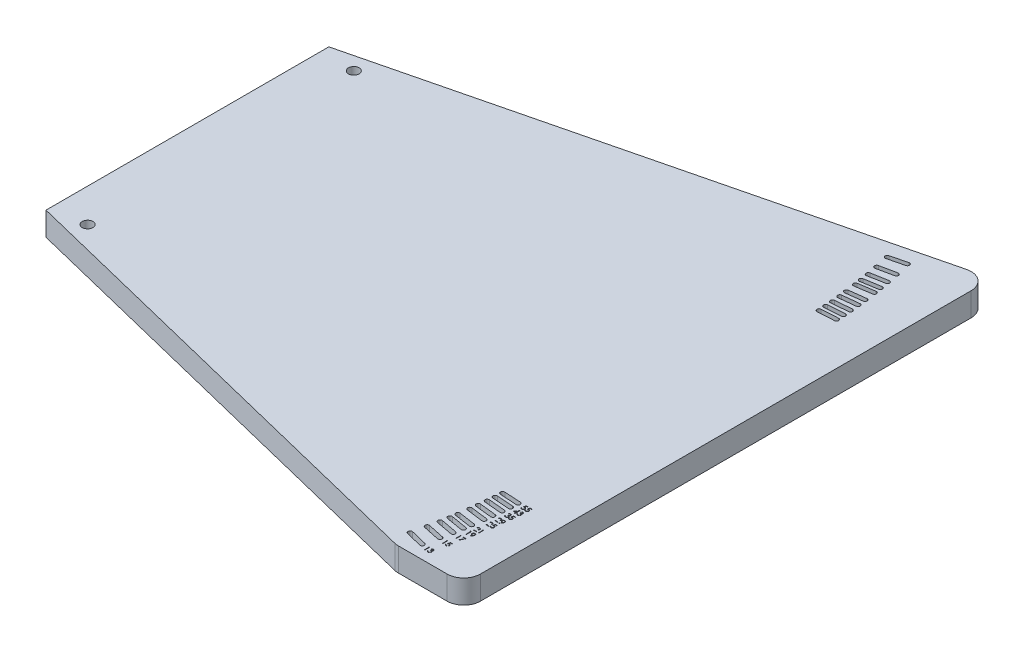
SolidWorks part; units mm, degrees
ref_plane "Front" through (0, 0, 0) normal (0, 0, 1) x (1, 0, 0)
ref_plane "Top" through (0, 0, 0) normal (0, 1, 0) x (1, 0, 0)
ref_plane "Right" through (0, 0, 0) normal (1, 0, 0) x (0, 0, -1)
sketch "Sketch1" plane through (0, 0, 0) normal (0, 1, 0) x (1, 0, 0)
  line L0 (0, 107.95) -> (0, -107.95)
  line L1 (0, -107.95) -> (406.4, -208.1174)
  line L2 (406.4, -208.1174) -> (406.4, 208.1174)
  line L3 (406.4, 208.1174) -> (0, 107.95)
  line L4 (25.4, 101.6) -> (25.4, -101.6) construction
  line L5 (25.4, 0) -> (0, 0) construction
  line L6 (25.4, 0) -> (406.4, 0) construction
  circle A0 centre (25.4, 101.6) radius 4.064
  circle A1 centre (25.4, -101.6) radius 4.064
  dimension "D1" = 8.128
  dimension "D2" = 203.2
  dimension "D3" = 103.846
  dimension "D4" = 25.4
  dimension "D5" = 406.4
  dimension "D6" = 215.9
extrude "Boss-Extrude1" add sketch "Sketch1" along normal blind 17.9832
sketch "Sketch2" plane through (0, 17.9832, 0) normal (0, 1, 0) x (1, 0, 0)
  line L0 (406.4, -208.1174) -> (406.4, 208.1174) construction
  line L1 (406.4, -195.4174) -> (354.8735, -195.4174)
  line L2 (406.4, -195.4174) -> (406.4, -208.1174)
  line L3 (406.4, -208.1174) -> (354.8735, -208.1174)
  line L4 (354.8735, -195.4174) -> (354.8735, -208.1174)
  line L5 (0, -107.95) -> (406.4, -208.1174) construction
  dimension "D1" = 12.7
extrude "Cut-Extrude1" cut sketch "Sketch2" against normal blind 17.9832
fillet "Fillet1" radius 12.7 3 edges at (406.4, 8.9916, -208.1174) (406.4, 8.9916, 195.4174) (354.8735, 8.9916, 195.4174)
sketch "Sketch3" plane through (0, 17.9832, 0) normal (0, 1, 0) x (1, 0, 0)
  line L0 (25.4, -101.6) -> (366.9196, -132.3373) construction
  line L1 (25.4, -101.6) -> (364.4701, -152.7066) construction
  line L2 (25.4, 101.6) -> (25.4, -101.6) construction
  line L3 (25.4, -101.6) -> (358.336, -183.6613) construction
  line L4 (25.4, 0) -> (406.4, 0) construction
  line L5 (406.4, -182.7174) -> (406.4, 191.9071) construction
  line L6 (25.4, -101.6) -> (363.6233, -158.0395) construction
  line L7 (25.4, -101.6) -> (365.5961, -144.5768) construction
  line L8 (25.4, -101.6) -> (367.7408, -121.1758) construction
  line L9 (25.4, -101.6) -> (360.8068, -172.8929) construction
  line L11 (364.5014, -185.181) -> (352.1705, -182.1417) construction
  line L12 (25.4, -101.6) -> (362.4615, -164.6077) construction
  line L13 (364.1215, -186.7223) -> (351.7906, -183.683)
  line L14 (364.8813, -183.6396) -> (352.5504, -180.6003)
  line L15 (367.018, -174.2132) -> (354.5956, -171.5727) construction
  line L16 (366.688, -175.766) -> (354.2655, -173.1255)
  line L17 (367.3481, -172.6603) -> (354.9256, -170.0199)
  line L18 (368.7033, -165.7745) -> (356.2196, -163.4409) construction
  line L19 (368.4116, -167.335) -> (355.9279, -165.0014)
  line L20 (368.9951, -164.2141) -> (356.5113, -161.8805)
  line L21 (371.8961, -145.3726) -> (359.2962, -143.7809) construction
  line L22 (371.6971, -146.9476) -> (359.0972, -145.3559)
  line L23 (372.095, -143.7976) -> (359.4952, -142.2059)
  line L27 (370.7492, -153.653) -> (358.191, -151.7602) construction
  line L28 (370.5126, -155.2228) -> (357.9544, -153.3299)
  line L29 (370.9858, -152.0832) -> (358.4276, -150.1904)
  line L30 (374.0804, -121.5383) -> (361.4011, -120.8132) construction
  line L31 (373.9898, -123.1232) -> (361.3105, -122.3981)
  line L32 (374.171, -119.9534) -> (361.4918, -119.2283)
  line L33 (373.244, -132.9065) -> (360.5951, -131.7681) construction
  line L34 (373.1017, -134.4876) -> (360.4528, -133.3492)
  line L35 (373.3863, -131.3254) -> (360.7375, -130.187)
  line L36 (369.8867, -159.0847) -> (357.3599, -156.9943) construction
  line L37 (369.6254, -160.6505) -> (357.0986, -158.5602)
  line L38 (370.148, -157.5188) -> (357.6212, -155.4285)
  line L55 (25.4, -101.6) -> (367.3852, -126.6301) construction
  line L68 (373.7183, -127.0936) -> (361.0522, -126.1666) construction
  line L69 (373.6024, -128.6769) -> (360.9363, -127.7498)
  line L70 (373.8342, -125.5104) -> (361.1681, -124.5833)
  line L71 (25.4, -101.6) -> (366.2899, -138.674) construction
  line L72 (372.6027, -139.3606) -> (359.9771, -137.9875) construction
  line L73 (372.431, -140.9388) -> (359.8055, -139.5657)
  line L74 (372.7743, -137.7824) -> (360.1488, -136.4093)
  arc A0 (364.1215, -186.7223) -> (364.8813, -183.6396) centre (364.5014, -185.181) ccw
  arc A1 (352.5504, -180.6003) -> (351.7906, -183.683) centre (352.1705, -182.1417) ccw
  arc A2 (366.688, -175.766) -> (367.3481, -172.6603) centre (367.018, -174.2132) ccw
  arc A3 (354.9256, -170.0199) -> (354.2655, -173.1255) centre (354.5956, -171.5727) ccw
  arc A4 (368.4116, -167.335) -> (368.9951, -164.2141) centre (368.7033, -165.7745) ccw
  arc A5 (356.5113, -161.8805) -> (355.9279, -165.0014) centre (356.2196, -163.4409) ccw
  arc A6 (371.6971, -146.9476) -> (372.095, -143.7976) centre (371.8961, -145.3726) ccw
  arc A7 (359.4952, -142.2059) -> (359.0972, -145.3559) centre (359.2962, -143.7809) ccw
  arc A10 (370.5126, -155.2228) -> (370.9858, -152.0832) centre (370.7492, -153.653) ccw
  arc A11 (358.4276, -150.1904) -> (357.9544, -153.3299) centre (358.191, -151.7602) ccw
  arc A12 (373.9898, -123.1232) -> (374.171, -119.9534) centre (374.0804, -121.5383) ccw
  arc A13 (361.4918, -119.2283) -> (361.3105, -122.3981) centre (361.4011, -120.8132) ccw
  arc A14 (373.1017, -134.4876) -> (373.3863, -131.3254) centre (373.244, -132.9065) ccw
  arc A15 (360.7375, -130.187) -> (360.4528, -133.3492) centre (360.5951, -131.7681) ccw
  arc A16 (369.6254, -160.6505) -> (370.148, -157.5188) centre (369.8867, -159.0847) ccw
  arc A17 (357.6212, -155.4285) -> (357.0986, -158.5602) centre (357.3599, -156.9943) ccw
  arc A32 (373.6024, -128.6769) -> (373.8342, -125.5104) centre (373.7183, -127.0936) ccw
  arc A33 (361.1681, -124.5833) -> (360.9363, -127.7498) centre (361.0522, -126.1666) ccw
  arc A34 (372.431, -140.9388) -> (372.7743, -137.7824) centre (372.6027, -139.3606) ccw
  arc A35 (360.1488, -136.4093) -> (359.8055, -139.5657) centre (359.9771, -137.9875) ccw
  point P18 (358.336, -183.6613)
  point P25 (360.8068, -172.8929)
  point P33 (362.4615, -164.6077)
  point P39 (365.5961, -144.5768)
  point P53 (364.4701, -152.7066)
  point P61 (367.7408, -121.1758)
  point P67 (366.9196, -132.3373)
  point P76 (363.6233, -158.0395)
  point P140 (367.3852, -126.6301)
  point P148 (366.2899, -138.674)
  dimension "D1" = 342.9
  dimension "D3" = 12
  dimension "D4" = 10.588
  dimension "D5" = 7.2
  dimension "D2" = 13.846
  dimension "D7" = 8.571
  dimension "D8" = 3.273
  dimension "D9" = 5.143
  dimension "D10" = 12.7
  dimension "D11" = 3.175
  dimension "D13" = 9.474
  dimension "D21" = 4.186
  dimension "D22" = 6.207
extrude "Magic Cut" cut sketch "Sketch3" against normal through all
mirror "Mirror1" about plane through (0, 0, 0) normal (0, 0, 1) of "Magic Cut"
sketch "Sketch5" plane through (0, 17.9832, 0) normal (0, 1, 0) x (1, 0, 0)
  line L0 (364.5014, -185.181) -> (367.6686, -188.2231) construction
  line L1 (368.7033, -165.7745) -> (372.0383, -168.6318) construction
  line L2 (367.018, -174.2132) -> (370.2816, -177.1517) construction
  line L3 (371.8961, -145.3726) -> (375.394, -148.0277) construction
  line L4 (369.8867, -159.0847) -> (373.2766, -161.8765) construction
  line L5 (374.0804, -121.5383) -> (377.752, -123.9476) construction
  line L6 (373.244, -132.9065) -> (376.8351, -135.4344) construction
  line L7 (373.7183, -127.0936) -> (377.351, -129.5611) construction
  line L8 (370.7492, -153.653) -> (374.1826, -156.3911) construction
  line L9 (372.6027, -139.3606) -> (376.1462, -141.9547) construction
  line L17 (364.5014, -185.181) -> (352.1705, -182.1417) construction
  line L18 (367.018, -174.2132) -> (354.5956, -171.5727) construction
  line L19 (368.7033, -165.7745) -> (356.2196, -163.4409) construction
  line L20 (369.8867, -159.0847) -> (357.3599, -156.9943) construction
  line L21 (371.8961, -145.3726) -> (359.2962, -143.7809) construction
  line L22 (372.6027, -139.3606) -> (359.9771, -137.9875) construction
  line L23 (370.7492, -153.653) -> (358.191, -151.7602) construction
  line L24 (374.0804, -121.5383) -> (361.4011, -120.8132) construction
  line L25 (373.244, -132.9065) -> (360.5951, -131.7681) construction
  line L26 (373.7183, -127.0936) -> (361.0522, -126.1666) construction
  circle A0 centre (25.4, -101.6) radius 353.06 construction
  text T0 "13"
  text T1 "15"
  text T2 "17"
  text T3 "19"
  text T4 "25"
  text T5 "29"
  text T6 "21"
  text T7 "55"
  text T8 "35"
  text T9 "43"
  dimension "D1" = 706.12
  dimension "D2" = 30
  dimension "D3" = 30
  dimension "D4" = 30
  dimension "D5" = 30
  dimension "D6" = 30
  dimension "D7" = 30
  dimension "D8" = 30
  dimension "D9" = 30
  dimension "D10" = 30
  dimension "D11" = 30
extrude "Cut-Extrude2" cut sketch "Sketch5" against normal blind 1.27
